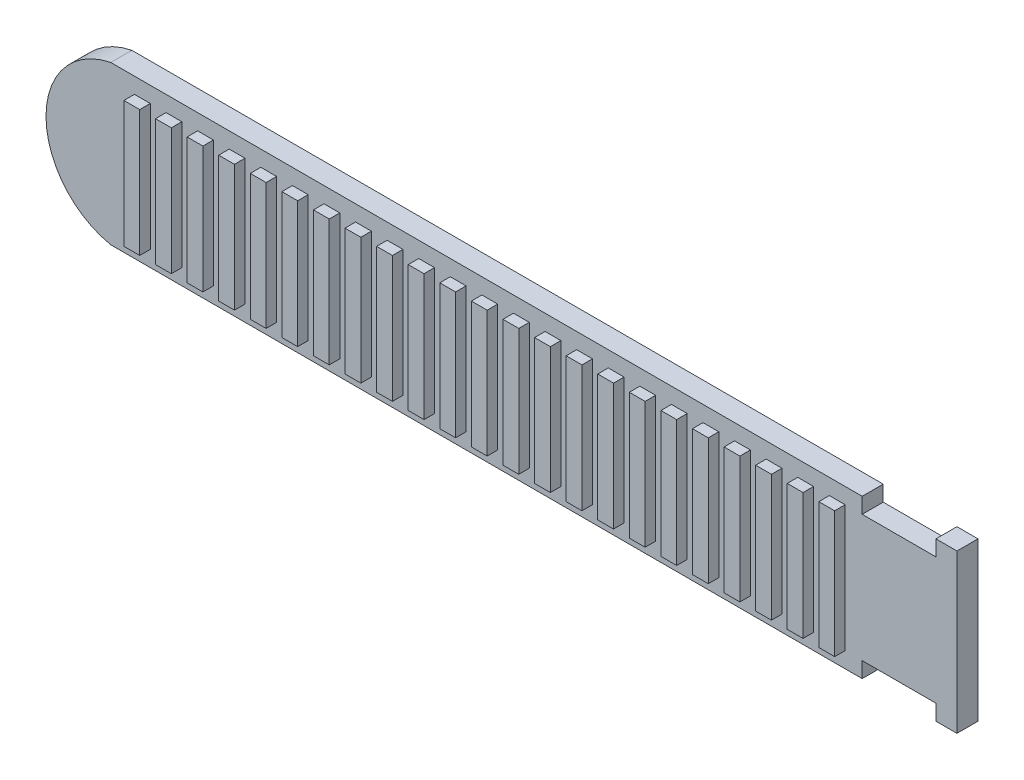
SolidWorks part; units mm, degrees
ref_plane "前视基准面" through (0, 0, 0) normal (0, 0, 1) x (1, 0, 0)
ref_plane "上视基准面" through (0, 0, 0) normal (0, 1, 0) x (1, 0, 0)
ref_plane "右视基准面" through (0, 0, 0) normal (1, 0, 0) x (0, 0, -1)
sketch "草图1" plane through (0, 0, 0) normal (0, 0, 1) x (1, 0, 0)
  line L0 (-51.5269, 0) -> (82.9283, 0) construction
  line L1 (0, 7.5) -> (71.3669, 7.5)
  line L2 (0, -7.5) -> (71.3669, -7.5)
  line L3 (71.3669, 7.5) -> (71.3669, 6.0168)
  line L4 (71.3669, 6.0168) -> (78.3669, 6.0168)
  line L5 (78.3669, 6.0168) -> (78.3669, 7.5)
  line L6 (78.3669, 7.5) -> (80.3669, 7.5)
  line L7 (80.3669, 7.5) -> (80.3669, -7.5)
  line L8 (78.3669, -7.5) -> (80.3669, -7.5)
  line L9 (78.3669, -6.0168) -> (78.3669, -7.5)
  line L10 (71.3669, -6.0168) -> (78.3669, -6.0168)
  line L11 (71.3669, -7.5) -> (71.3669, -6.0168)
  arc A1 (0, 7.5) -> (0, -7.5) centre (1.4961, 0) ccw
  point P14 (80.3669, 0)
  dimension "D2" = 15
  dimension "D3" = 1.4832
  dimension "D4" = 7
  dimension "D5" = 2
extrude "凸台-拉伸1" add sketch "草图1" along normal blind 2
sketch "草图2" plane through (0, 0, 2) normal (0, 0, 1) x (1, 0, 0)
  line L0 (0, 0) -> (80.3669, 0) construction
  line L1 (80.3669, -7.5) -> (80.3669, 7.5) construction
  line L2 (71.3669, 7.5) -> (0, 7.5) construction
  line L3 (2.25, 6) -> (3.75, 6)
  line L4 (2.25, 6) -> (2.25, -6)
  line L5 (2.25, -6) -> (3.75, -6)
  line L6 (3.75, 6) -> (3.75, -6)
  line L7 (2.25, 6) -> (3.75, -6) construction
  line L8 (2.25, -6) -> (3.75, 6) construction
  line L9 (5.25, 6) -> (5.25, -6)
  line L10 (5.25, 6) -> (6.75, 6)
  line L11 (6.75, 6) -> (6.75, -6)
  line L12 (5.25, -6) -> (6.75, -6)
  line L13 (8.25, 6) -> (8.25, -6)
  line L14 (8.25, 6) -> (9.75, 6)
  line L15 (9.75, 6) -> (9.75, -6)
  line L16 (8.25, -6) -> (9.75, -6)
  line L17 (11.25, 6) -> (11.25, -6)
  line L18 (11.25, 6) -> (12.75, 6)
  line L19 (12.75, 6) -> (12.75, -6)
  line L20 (11.25, -6) -> (12.75, -6)
  line L21 (14.25, 6) -> (14.25, -6)
  line L22 (14.25, 6) -> (15.75, 6)
  line L23 (15.75, 6) -> (15.75, -6)
  line L24 (14.25, -6) -> (15.75, -6)
  line L25 (17.25, 6) -> (17.25, -6)
  line L26 (17.25, 6) -> (18.75, 6)
  line L27 (18.75, 6) -> (18.75, -6)
  line L28 (17.25, -6) -> (18.75, -6)
  line L29 (20.25, 6) -> (20.25, -6)
  line L30 (20.25, 6) -> (21.75, 6)
  line L31 (21.75, 6) -> (21.75, -6)
  line L32 (20.25, -6) -> (21.75, -6)
  line L33 (23.25, 6) -> (23.25, -6)
  line L34 (23.25, 6) -> (24.75, 6)
  line L35 (24.75, 6) -> (24.75, -6)
  line L36 (23.25, -6) -> (24.75, -6)
  line L37 (26.25, 6) -> (26.25, -6)
  line L38 (26.25, 6) -> (27.75, 6)
  line L39 (27.75, 6) -> (27.75, -6)
  line L40 (26.25, -6) -> (27.75, -6)
  line L41 (29.25, 6) -> (29.25, -6)
  line L42 (29.25, 6) -> (30.75, 6)
  line L43 (30.75, 6) -> (30.75, -6)
  line L44 (29.25, -6) -> (30.75, -6)
  line L45 (32.25, 6) -> (32.25, -6)
  line L46 (32.25, 6) -> (33.75, 6)
  line L47 (33.75, 6) -> (33.75, -6)
  line L48 (32.25, -6) -> (33.75, -6)
  line L49 (35.25, 6) -> (35.25, -6)
  line L50 (35.25, 6) -> (36.75, 6)
  line L51 (36.75, 6) -> (36.75, -6)
  line L52 (35.25, -6) -> (36.75, -6)
  line L53 (38.25, 6) -> (38.25, -6)
  line L54 (38.25, 6) -> (39.75, 6)
  line L55 (39.75, 6) -> (39.75, -6)
  line L56 (38.25, -6) -> (39.75, -6)
  line L57 (41.25, 6) -> (41.25, -6)
  line L58 (41.25, 6) -> (42.75, 6)
  line L59 (42.75, 6) -> (42.75, -6)
  line L60 (41.25, -6) -> (42.75, -6)
  line L61 (44.25, 6) -> (44.25, -6)
  line L62 (44.25, 6) -> (45.75, 6)
  line L63 (45.75, 6) -> (45.75, -6)
  line L64 (44.25, -6) -> (45.75, -6)
  line L65 (47.25, 6) -> (47.25, -6)
  line L66 (47.25, 6) -> (48.75, 6)
  line L67 (48.75, 6) -> (48.75, -6)
  line L68 (47.25, -6) -> (48.75, -6)
  line L69 (50.25, 6) -> (50.25, -6)
  line L70 (50.25, 6) -> (51.75, 6)
  line L71 (51.75, 6) -> (51.75, -6)
  line L72 (50.25, -6) -> (51.75, -6)
  line L73 (53.25, 6) -> (53.25, -6)
  line L74 (53.25, 6) -> (54.75, 6)
  line L75 (54.75, 6) -> (54.75, -6)
  line L76 (53.25, -6) -> (54.75, -6)
  line L77 (56.25, 6) -> (56.25, -6)
  line L78 (56.25, 6) -> (57.75, 6)
  line L79 (57.75, 6) -> (57.75, -6)
  line L80 (56.25, -6) -> (57.75, -6)
  line L81 (59.25, 6) -> (59.25, -6)
  line L82 (59.25, 6) -> (60.75, 6)
  line L83 (60.75, 6) -> (60.75, -6)
  line L84 (59.25, -6) -> (60.75, -6)
  line L85 (62.25, 6) -> (62.25, -6)
  line L86 (62.25, 6) -> (63.75, 6)
  line L87 (63.75, 6) -> (63.75, -6)
  line L88 (62.25, -6) -> (63.75, -6)
  line L89 (65.25, 6) -> (65.25, -6)
  line L90 (65.25, 6) -> (66.75, 6)
  line L91 (66.75, 6) -> (66.75, -6)
  line L92 (65.25, -6) -> (66.75, -6)
  line L93 (68.25, 6) -> (68.25, -6)
  line L94 (68.25, 6) -> (69.75, 6)
  line L95 (69.75, 6) -> (69.75, -6)
  line L96 (68.25, -6) -> (69.75, -6)
  point P5 (3, 0)
  dimension "D1" = 3
  dimension "D2" = 1.5
  dimension "D3" = 1.5
  dimension "D4" = 23
extrude "凸台-拉伸2" add sketch "草图2" along normal blind 1
scale "缩放比例1" scale about centroid uniform scaling yes scale factor 1.6
